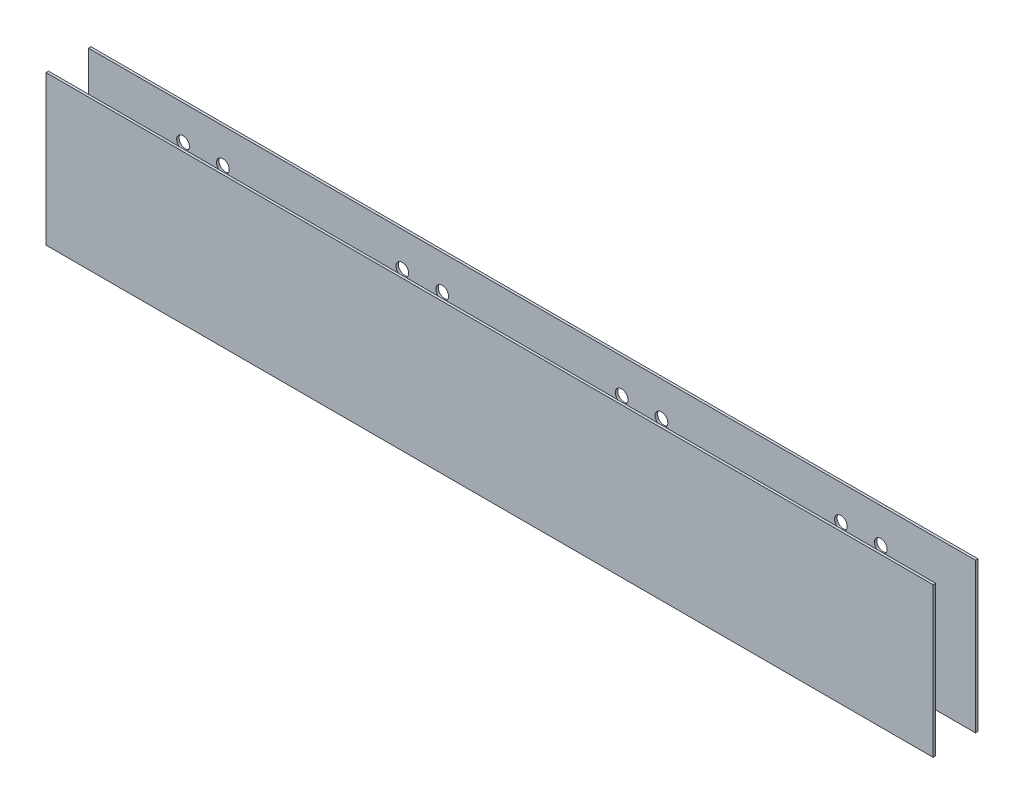
SolidWorks part; units mm, degrees
ref_plane "Front Plane" through (0, 0, 0) normal (0, 0, 1) x (1, 0, 0)
ref_plane "Top Plane" through (0, 0, 0) normal (0, 1, 0) x (1, 0, 0)
ref_plane "Right Plane" through (0, 0, 0) normal (1, 0, 0) x (0, 0, -1)
sketch "Sketch1" plane through (0, 0, 0) normal (0, 1, 0) x (1, 0, 0)
  line L0 (0, 0) -> (67756.1113, 0) construction
  line L1 (0, 0) -> (0, -50000) construction
  line L7 (-890, 45) -> (890, 45)
  line L12 (-890, 45) -> (-890, 40)
  line L13 (-890, 40) -> (890, 40)
  line L14 (890, 45) -> (890, 40)
  line L15 (-890, 45) -> (890, 40) construction
  line L16 (-890, 40) -> (890, 45) construction
  line L17 (-890, -40) -> (890, -40)
  line L18 (-890, -40) -> (-890, -45)
  line L19 (-890, -45) -> (890, -45)
  line L20 (890, -40) -> (890, -45)
  line L21 (-890, -40) -> (890, -45) construction
  line L22 (-890, -45) -> (890, -40) construction
  point P3 (-853.3929, 31.0714)
  point P4 (0, 42.5)
  point P12 (0, -42.5)
  point P17 (0, 0)
  dimension "D1" = 5
  dimension "D2" = 5
  dimension "D3" = 1780
  dimension "D4" = 1780
  dimension "D5" = 40
  dimension "D6" = 40
extrude "Boss-Extrude1" add sketch "Sketch1" along normal mid plane 300
sketch "Sketch2" plane through (0, 0, 45) normal (0, 0, 1) x (1, 0, 0)
  line L0 (-963.5737, 80) -> (1004.6165, 80) construction
  line L2 (-890, 150) -> (-890, -150) construction
  line L3 (-700.1, 80) -> (-260.1, 80) construction
  line L4 (890, 150) -> (890, -150) construction
  line L5 (-890, 150) -> (890, 150) construction
  circle A1 centre (-700.1, 80) radius 12.75
  circle A2 centre (-620.1, 80) radius 12.75
  circle A3 centre (-260.1, 80) radius 12.75
  circle A4 centre (-180.1, 80) radius 12.75
  circle A5 centre (179.9, 80) radius 12.75
  circle A6 centre (259.9, 80) radius 12.75
  circle A7 centre (619.9, 80) radius 12.75
  circle A8 centre (699.9, 80) radius 12.75
  dimension "D2" = 25.5
  dimension "D3" = 25.5
  dimension "D4" = 80
  dimension "D5" = 189.9
  dimension "D6" = 440
  dimension "D7" = 360
  dimension "D8" = 360
  dimension "D9" = 360
  dimension "D10" = 190.1
  dimension "D11" = 70
extrude "Cut-Extrude1" cut sketch "Sketch2" against normal blind 33 and the other way blind 39 from surface at -85 starting at face at (0, 0, -40)
